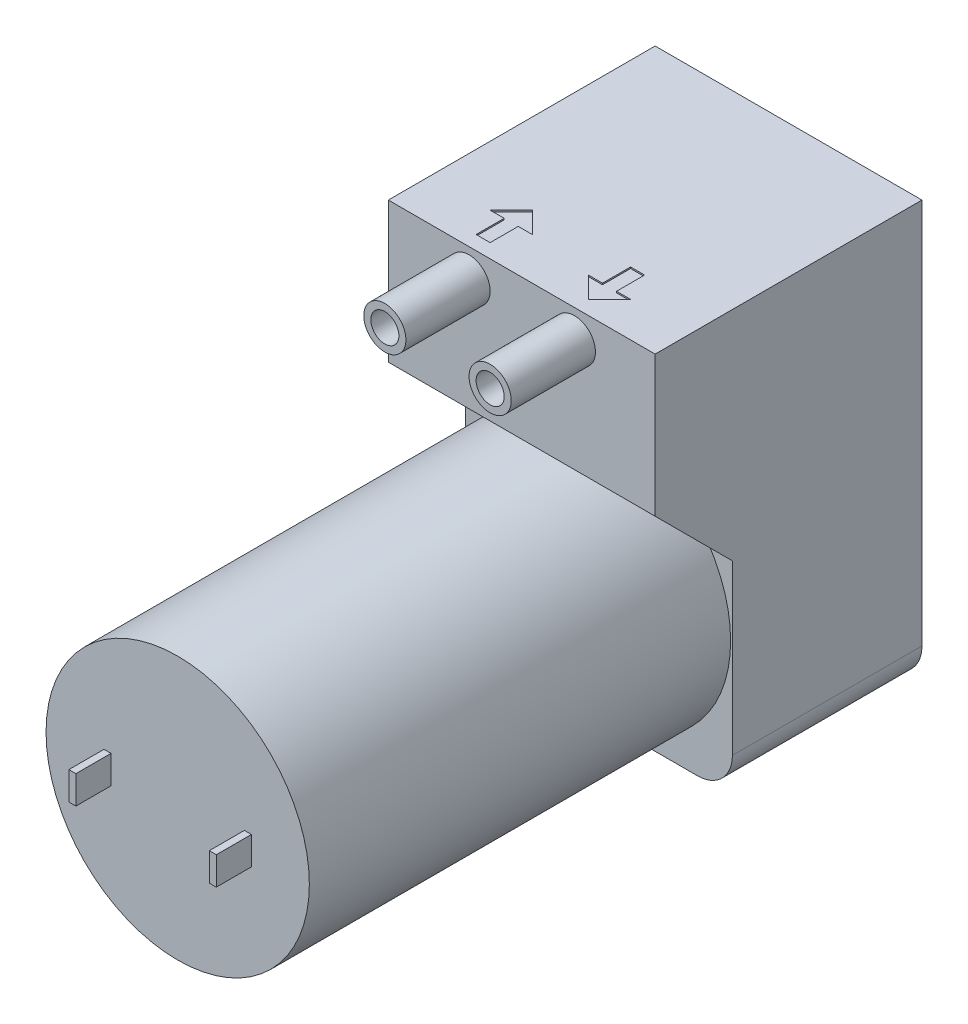
SolidWorks part; units mm, degrees
material "PP copolymère"
ref_plane "Plan de face" through (0, 0, 0) normal (0, 0, 1) x (1, 0, 0)
ref_plane "Plan de dessus" through (0, 0, 0) normal (0, 1, 0) x (1, 0, 0)
ref_plane "Plan de droite" through (0, 0, 0) normal (1, 0, 0) x (0, 0, -1)
sketch "Sketch1" plane through (0, 0, 0) normal (0, 0, 1) x (1, 0, 0)
  line L0 (-19, -19) -> (-19, 41)
  line L1 (-19, 41) -> (19, 41)
  line L2 (19, 41) -> (19, -19)
  line L3 (-19, -19) -> (19, -19)
  line L4 (0, 0) -> (0, -19) construction
  line L5 (0, 0) -> (-19, 0) construction
  dimension "D1" = 38
  dimension "D2" = 60
extrude "Extrude1" add sketch "Sketch1" along normal blind 38
sketch "Sketch2" plane through (19, 0, 0) normal (1, 0, 0) x (0, 0, -1)
  line L0 (0, -19) -> (0, 41) construction
  line L1 (-38, -19) -> (-27, -19)
  line L2 (-38, -19) -> (-38, 21)
  line L3 (-38, 21) -> (-27, 10)
  line L4 (-27, -19) -> (-27, 10)
  dimension "D1" = 27
  dimension "D2" = 45
  dimension "D3" = 40
extrude "Extrude2" cut sketch "Sketch2" against normal through all
fillet "Fillet1" radius 5 2 edges at (-19, -19, 13.5) (19, -19, 13.5)
sketch "Sketch3" plane through (0, 0, 27) normal (0, 0, 1) x (1, 0, 0)
  circle A0 centre (0, 0) radius 18.75
  dimension "D1" = 37.5
extrude "Extrude3" add sketch "Sketch3" along normal blind 60 separate body
sketch "Sketch4" plane through (0, 0, 38) normal (0, 0, 1) x (1, 0, 0)
  line L0 (19, 41) -> (-19, 41) construction
  line L1 (0, 41) -> (0, 27.3588) construction
  circle A0 centre (-7.5, 37) radius 3
  circle A1 centre (-7.5, 37) radius 2
  circle A2 centre (7.5, 37) radius 2
  circle A3 centre (7.5, 37) radius 3
  dimension "D1" = 1
  dimension "D2" = 6
  dimension "D3" = 4
  dimension "D4" = 15
extrude "Extrude4" add sketch "Sketch4" along normal blind 12
sketch "Sketch5" plane through (0, 41, 0) normal (0, 1, 0) x (1, 0, 0)
  line L0 (-8.5, -36) -> (-8.5, -32)
  line L1 (-8.5, -32) -> (-10.5, -32)
  line L2 (-10.5, -32) -> (-7.5, -29)
  line L3 (-7.5, -29) -> (-4.5, -32)
  line L4 (-4.5, -32) -> (-6.5, -32)
  line L5 (-6.5, -32) -> (-6.5, -36)
  line L6 (-6.5, -36) -> (-8.5, -36)
  line L7 (6.5, -29) -> (8.5, -29)
  line L8 (8.5, -29) -> (8.5, -33)
  line L9 (8.5, -33) -> (10.5, -33)
  line L10 (10.5, -33) -> (7.5, -36)
  line L11 (7.5, -36) -> (4.5, -33)
  line L12 (4.5, -33) -> (6.5, -33)
  line L13 (6.5, -33) -> (6.5, -29)
  line L14 (0, -38) -> (0, -29) construction
  line L15 (19, -38) -> (-19, -38) construction
  line L16 (-7.5, -29) -> (7.5, -29) construction
  dimension "D1" = 15
  dimension "D2" = 2
  dimension "D3" = 2
  dimension "D4" = 7
extrude "Extrude5" cut sketch "Sketch5" against normal blind 0.2
sketch "Sketch6" plane through (0, 0, 87) normal (0, 0, 1) x (1, 0, 0)
  line L0 (-10, 0) -> (10, 0) construction
  line L1 (-10.5, 2) -> (-9.5, 2)
  line L2 (-10.5, 2) -> (-10.5, -2)
  line L3 (-9.5, 2) -> (-9.5, -2)
  line L4 (-10.5, -2) -> (-9.5, -2)
  line L5 (-10.5, 2) -> (-9.5, -2) construction
  line L6 (-9.5, 2) -> (-10.5, -2) construction
  line L7 (10.5, 2) -> (9.5, 2)
  line L8 (10.5, 2) -> (10.5, -2)
  line L9 (9.5, 2) -> (9.5, -2)
  line L10 (10.5, -2) -> (9.5, -2)
  line L11 (10.5, 2) -> (9.5, -2) construction
  line L12 (9.5, 2) -> (10.5, -2) construction
  dimension "D1" = 1
  dimension "D2" = 4
  dimension "D3" = 20
extrude "Extrude6" add sketch "Sketch6" along normal blind 5
